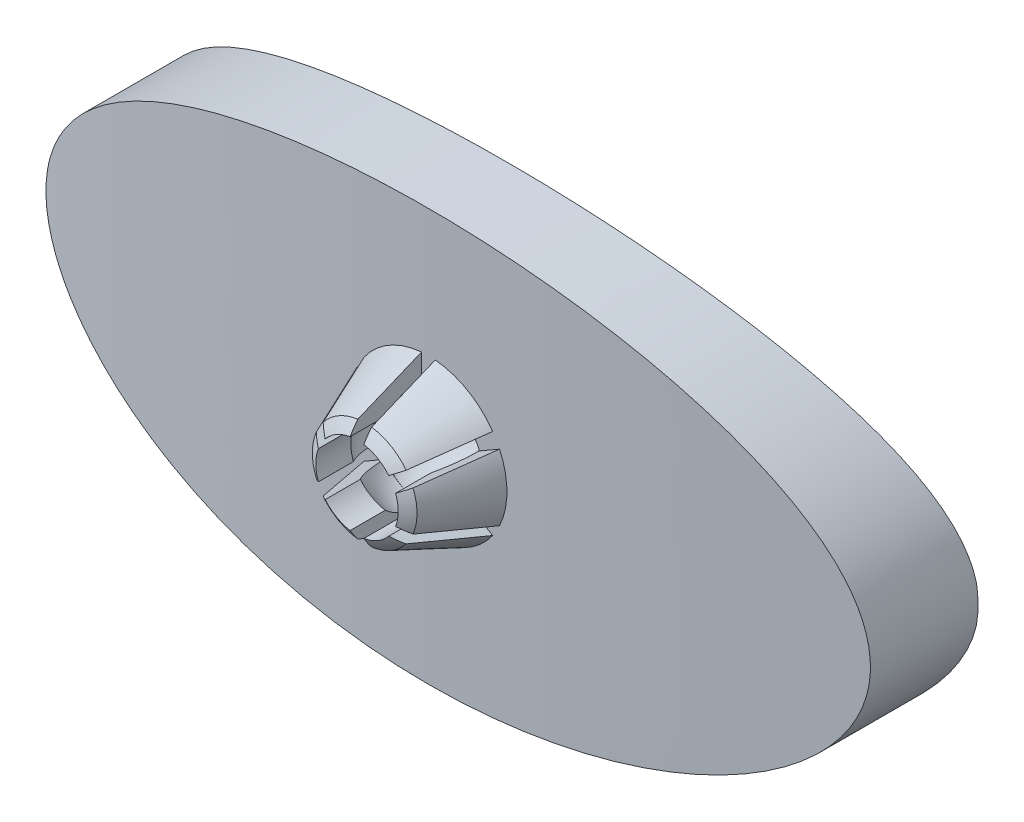
SolidWorks part; units mm, degrees
ref_plane "Plan de face" through (0, 0, 0) normal (0, 0, 1) x (1, 0, 0)
ref_plane "Plan de dessus" through (0, 0, 0) normal (0, 1, 0) x (1, 0, 0)
ref_plane "Plan de droite" through (0, 0, 0) normal (1, 0, 0) x (0, 0, -1)
sketch "Esquisse1" plane through (0, 0, 0) normal (0, 0, 1) x (1, 0, 0)
  line L0 (-12.9385, 0) -> (-52.9385, 0) construction
  ellipse E0 centre (-32.9385, 0) end of major axis (-62.9385, 0) minor radius 15
  dimension "D1" = 40
  dimension "D2" = 60
  dimension "D3" = 30
extrude "Boss.-Extru.1" add sketch "Esquisse1" along normal blind 10
sketch "Esquisse2" plane through (0, 0, 0) normal (0, 1, 0) x (1, 0, 0)
  line L0 (-32.9385, 9.5661) -> (-32.9385, 23.3608) construction
  line L1 (-32.9385, 23.3608) -> (-32.9385, 19.1382) construction
  line L2 (-90.0895, 4.5691) -> (24.2125, 4.5691) construction
  line L3 (8.5234, 9.5661) -> (-74.4004, 9.5661) construction
  line L5 (-64.5713, 0.6481) -> (-64.5713, -7.5648)
  line L6 (-1.336, 0.6362) -> (-1.336, -7.5699)
  line L8 (-95.0982, 25.6848) -> (40.731, 25.6848)
  line L9 (-95.0982, 25.6848) -> (-95.0982, -23.4524)
  line L10 (-95.0982, -23.4524) -> (40.731, -23.4524)
  line L11 (40.731, 25.6848) -> (40.731, -23.4524)
  ellipse E2 centre (-32.9385, 4.5691) end of major axis (24.2125, 4.5691) minor radius 14.5691 (-64.5713, -7.5648) -> (-1.336, -7.5699) ccw
  ellipse E3 centre (-32.9385, 9.5661) end of major axis (8.5234, 9.5661) minor radius 13.7948 (-64.5713, 0.6481) -> (-1.336, 0.6362) ccw
extrude "Enlèv. mat.-Extru.1" cut sketch "Esquisse2" against normal through all and the other way through all
ref_plane "Plan1" through (0, 0, 10) normal (0, 0, 1) x (1, 0, 0)
sketch "Esquisse3" plane through (0, 0, 10) normal (0, 0, 1) x (1, 0, 0)
  line L0 (-32.9385, 15) -> (-32.9385, -15) construction
  line L1 (-32.9385, 0) -> (0, 0) construction
  line L2 (-32.9385, 6) -> (-32.9385, 4)
  line L3 (-32.9385, -4) -> (-32.9385, -6)
  arc A0 (-32.9385, 6) -> (-32.9385, -6) centre (-32.9385, 0) ccw
  arc A1 (-32.9385, 4) -> (-32.9385, -4) centre (-32.9385, 0) ccw
  ellipse E0 centre (-32.9385, 0) end of major axis (-62.9385, 0) minor radius 15 construction
  dimension "D1" = 4
  dimension "D2" = 6
revolve "Révolution4" add sketch "Esquisse3" angle 180 about L0
sketch "Esquisse4" plane through (0, 0, 10) normal (0, 0, 1) x (1, 0, 0)
  circle A0 centre (-32.9385, 0) radius 3
  dimension "D1" = 6
extrude "Enlèv. mat.-Extru.2" cut sketch "Esquisse4" along normal blind 10
sketch "Esquisse6" plane through (0, 0, 10) normal (0, 0, 1) x (1, 0, 0)
  line L0 (-32.9385, 0) -> (-32.9385, 13.5992) construction
  line L2 (-33.4385, 0.866) -> (-33.4385, -0.866) construction
  line L3 (-33.4385, 6) -> (-32.4385, 6)
  line L4 (-32.4385, 0.866) -> (-32.4385, -0.866) construction
  line L5 (-31.9385, 0) -> (-33.4385, -0.866) construction
  line L6 (-32.4385, -7.7001) -> (-33.4385, -7.7001)
  line L7 (-33.4385, -7.7001) -> (-33.4385, -0.866)
  line L8 (-24.7776, 4.7117) -> (-26.0833, 3.9579) construction
  line L9 (-39.2758, 3.6589) -> (-26.6012, -3.6589) construction
  line L10 (-38.631, 3.8639) -> (-39.131, 2.9979)
  line L11 (-39.131, 2.9979) -> (-33.9385, 0)
  line L12 (-26.4432, -4.3274) -> (-25.9432, -3.4614)
  line L13 (-25.9432, -3.4614) -> (-31.9385, 0)
  line L14 (-26.3333, 4.3909) -> (-32.4385, 0.866)
  line L15 (-40.0912, -3.5523) -> (-39.5912, -4.4183)
  line L16 (-39.5912, -4.4183) -> (-33.4385, -0.866)
  line L17 (-25.8333, 3.5248) -> (-26.3333, 4.3909)
  line L18 (-33.4385, 0.866) -> (-33.4385, 6)
  line L19 (-33.4385, 0.866) -> (-38.631, 3.8639)
  line L20 (-32.4385, 0.866) -> (-32.4385, 6)
  line L21 (-32.4385, 0.866) -> (-33.9385, 0) construction
  line L22 (-33.4385, 0.866) -> (-31.9385, 0) construction
  line L23 (-32.4385, 0.2887) -> (-41.0994, -4.7117) construction
  line L24 (-31.9385, 0) -> (-25.8333, 3.5248)
  line L25 (-33.9385, 0) -> (-40.0912, -3.5523)
  line L26 (-32.4385, -0.866) -> (-33.9385, 0) construction
  line L27 (-32.9385, 0) -> (-26.0833, 3.9579) construction
  line L29 (-32.4385, -0.866) -> (-32.4385, -7.7001)
  line L30 (-32.4385, -0.866) -> (-26.4432, -4.3274)
  dimension "D1" = 1
  dimension "D3" = 60
  dimension "D4" = 60
extrude "Enlèv. mat.-Extru.3" cut sketch "Esquisse6" along normal blind 10
sketch "Esquisse7" plane through (0, 0, 0) normal (0, 1, 0) x (1, 0, 0)
  line L0 (-32.9385, -6) -> (-32.9385, -14)
  arc A0 (-32.9385, -6) -> (-32.9385, -14) centre (-32.9385, -10) ccw
  dimension "D1" = 8
revolve "Enlèvement de matière-Révolution1" cut sketch "Esquisse7" angle 360 about L0
sketch "Esquisse8" plane through (0, 0, 0) normal (0, 1, 0) x (1, 0, 0)
  line L0 (-32.9385, -10) -> (-32.9385, -33.7614) construction
  line L1 (-42.9451, -10) -> (-38.6525, -10)
  line L2 (-38.6525, -10) -> (-35.8107, -16.9136)
  line L3 (-35.8107, -16.9136) -> (-42.9451, -16.9136)
  line L4 (-42.9451, -16.9136) -> (-42.9451, -10)
  line L5 (-38.3666, -10) -> (-38.9385, -10) construction
revolve "Enlèvement de matière-Révolution2" cut sketch "Esquisse8" angle 360 about L0
